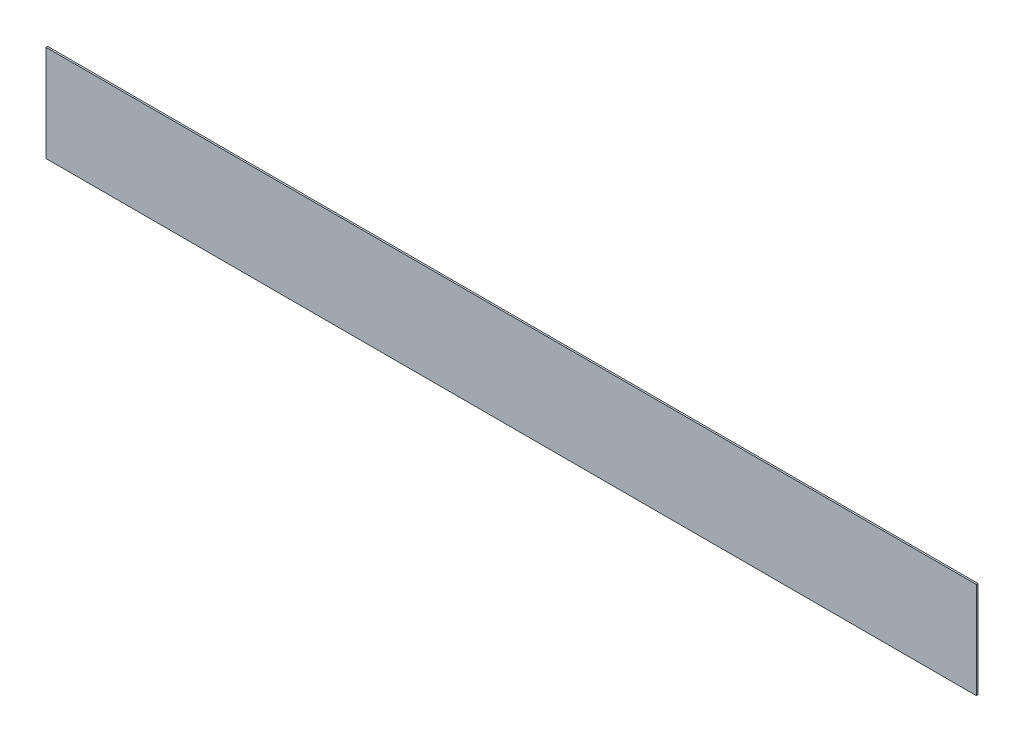
SolidWorks part; units mm, degrees
ref_plane "Front Plane" through (0, 0, 0) normal (0, 0, 1) x (1, 0, 0)
ref_plane "Top Plane" through (0, 0, 0) normal (0, 1, 0) x (1, 0, 0)
ref_plane "Right Plane" through (0, 0, 0) normal (1, 0, 0) x (0, 0, -1)
sketch "Sketch1" plane through (0, 0, 0) normal (0, 0, 1) x (1, 0, 0)
  line L1 (0, 0) -> (700, 0)
  line L2 (0, 0) -> (0, 72.46)
  line L3 (0, 72.46) -> (700, 72.46)
  line L4 (700, 0) -> (700, 72.46)
  dimension "D1" = 72.46
  dimension "D2" = 700
extrude "Boss-Extrude1" add sketch "Sketch1" along normal blind 1.27
